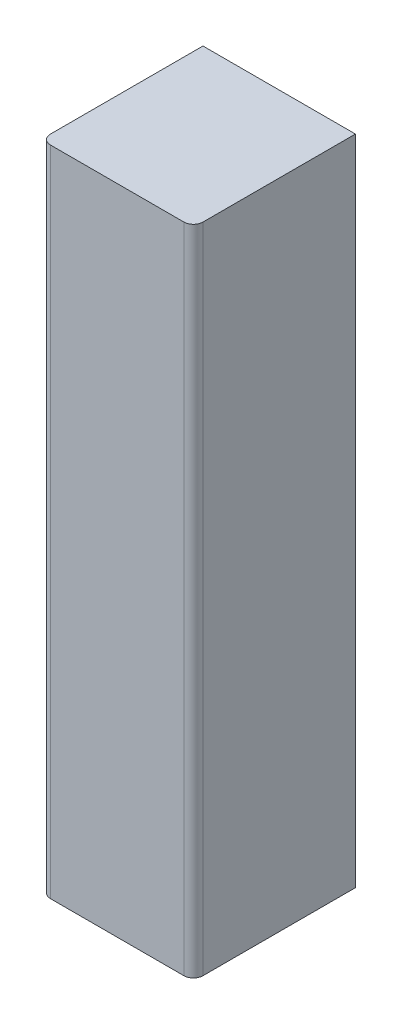
SolidWorks part; units mm, degrees
ref_plane "前视基准面" through (0, 0, 0) normal (0, 0, 1) x (1, 0, 0)
ref_plane "上视基准面" through (0, 0, 0) normal (0, 1, 0) x (1, 0, 0)
ref_plane "右视基准面" through (0, 0, 0) normal (1, 0, 0) x (0, 0, -1)
sketch "草图1" plane through (0, 0, 0) normal (0, 0, 1) x (1, 0, 0)
  line L0 (0, 48.626) -> (0, -83.7004) construction
  line L1 (-92.2698, 0) -> (95.8569, 0) construction
  line L2 (-8, 34.25) -> (8, 34.25)
  line L3 (-8, 34.25) -> (-8, -34.25)
  line L4 (-8, -34.25) -> (8, -34.25)
  line L5 (8, -34.25) -> (8, 34.25)
  dimension "D1" = 16
  dimension "D2" = 68.5
extrude "拉伸1" add sketch "草图1" along normal blind 0.1
sketch "草图2" plane through (0, 0, 0.1) normal (0, 0, 1) x (1, 0, 0)
  line L0 (0, 37.5456) -> (0, -35.199) construction
  line L1 (-34.3867, 0) -> (34.7477, 0) construction
  line L2 (-8, 34.25) -> (8, 34.25)
  line L3 (-8, 34.25) -> (-8, -34.25)
  line L4 (-8, -34.25) -> (8, -34.25)
  line L5 (8, -34.25) -> (8, 34.25)
  dimension "D1" = 16
  dimension "D2" = 68.5
extrude "拉伸2" add sketch "草图2" along normal blind 16.9
fillet "圆角1" radius 1 2 edges at (-8, 0, 17) (8, 0, 17)
